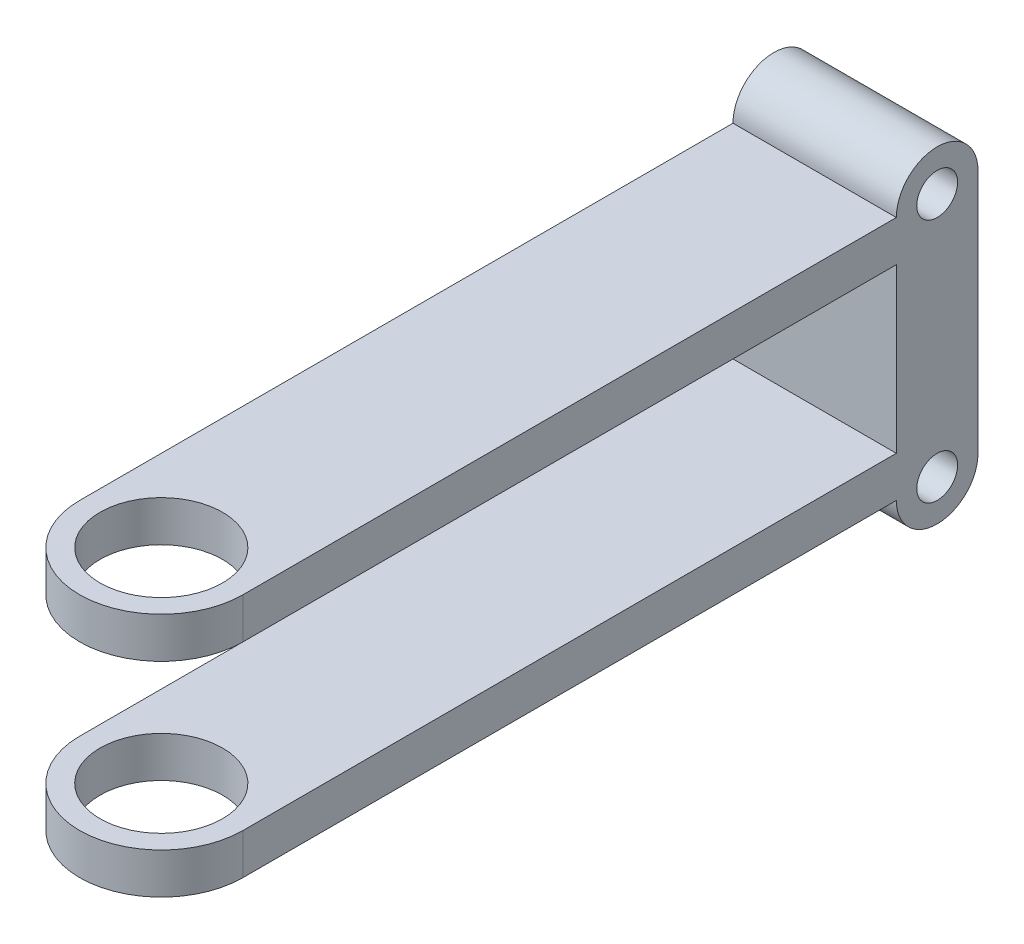
SolidWorks part; units mm, degrees
material "自定义塑料"
ref_plane "前视基准面" through (0, 0, 0) normal (0, 0, 1) x (1, 0, 0)
ref_plane "上视基准面" through (0, 0, 0) normal (0, 1, 0) x (1, 0, 0)
ref_plane "右视基准面" through (0, 0, 0) normal (1, 0, 0) x (0, 0, -1)
sketch "草图1" plane through (0, 0, 0) normal (0, 1, 0) x (1, 0, 0)
  line L0 (20, 0) -> (20, 170)
  line L1 (-20, 0) -> (-20, 170)
  line L2 (-20, 170) -> (20, 170)
  arc A0 (-20, 0) -> (20, 0) centre (0, 0) ccw
  circle A1 centre (0, 0) radius 15
  point P8 (0, 0)
extrude "凸台-拉伸1" add sketch "草图1" along normal blind 60
sketch "草图2" plane through (0, 0, -170) normal (0, 0, -1) x (-1, 0, 0)
  line L1 (-20, 60) -> (-20, 0) construction
  line L2 (20, 60) -> (20, 0) construction
  line L3 (-20, 50) -> (20, 50)
  line L4 (-20, 50) -> (-20, 10)
  line L5 (-20, 10) -> (20, 10)
  line L6 (20, 50) -> (20, 10)
extrude "切除-拉伸1" cut sketch "草图2" against normal blind 190
sketch "草图3" plane through (0, 10, 0) normal (0, 1, 0) x (1, 0, 0)
  line L0 (-20, 0) -> (-20, 170) construction
  line L2 (20, 170) -> (20, 160)
  line L3 (20, 160) -> (-20, 160)
  line L4 (-20, 170) -> (-20, 160)
  line L7 (20, 170) -> (20, 180)
  line L8 (20, 180) -> (-20, 180)
  line L9 (-20, 170) -> (-20, 180)
extrude "凸台-拉伸2" add sketch "草图3" along normal blind 50 and the other way blind 10
sketch "草图4" plane through (-20, 0, 0) normal (-1, 0, 0) x (0, 0, 1)
  line L0 (-180, 0) -> (0, 0) construction
  circle A0 centre (-170, 0) radius 10
  circle A1 centre (-170, 60) radius 10
extrude "凸台-拉伸3" add sketch "草图4" against normal blind 40
sketch "草图5" plane through (-20, 0, 0) normal (-1, 0, 0) x (0, 0, 1)
  circle A0 centre (-170, 0) radius 5
  circle A1 centre (-170, 60) radius 5
extrude "切除-拉伸3" cut sketch "草图5" against normal blind 40
